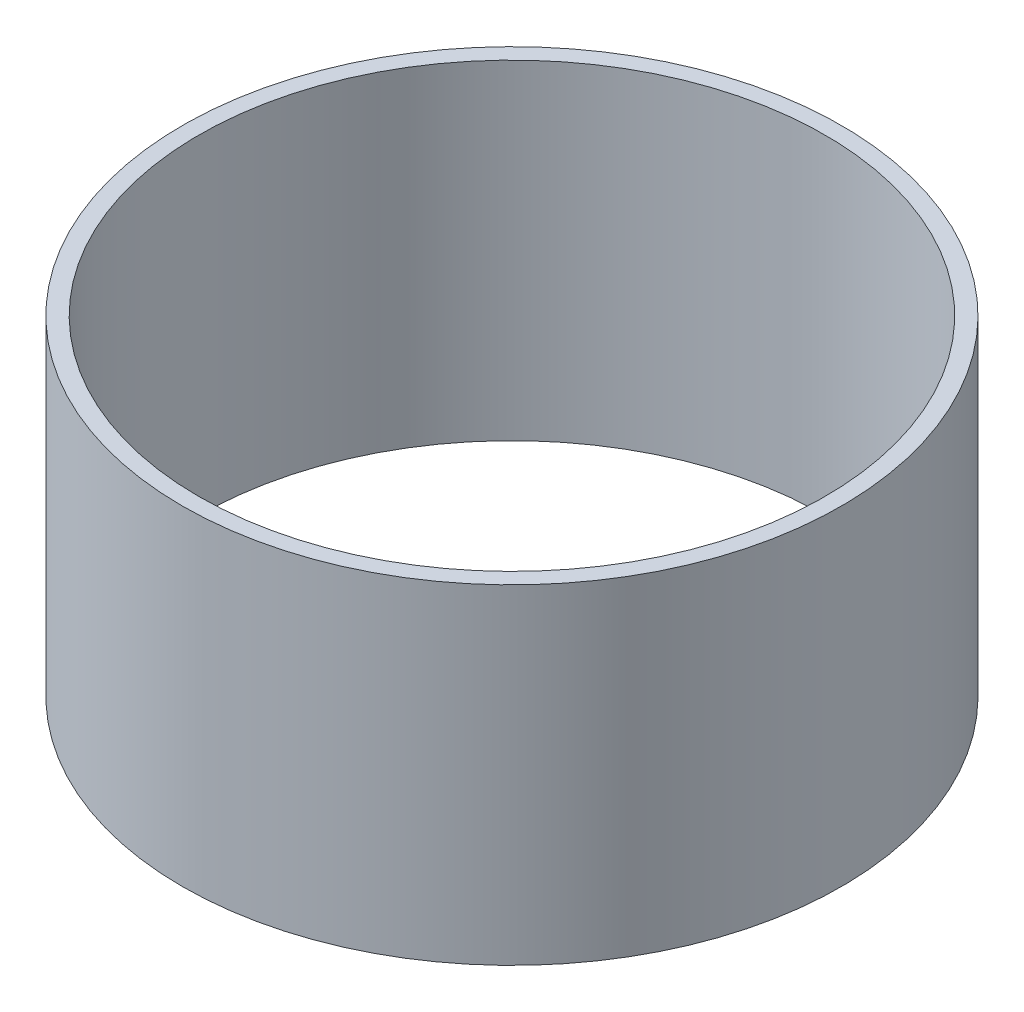
SolidWorks part; units mm, degrees
ref_plane "Front Plane" through (0, 0, 0) normal (0, 0, 1) x (1, 0, 0)
ref_plane "Top Plane" through (0, 0, 0) normal (0, 1, 0) x (1, 0, 0)
ref_plane "Right Plane" through (0, 0, 0) normal (1, 0, 0) x (0, 0, -1)
sketch "Sketch2" plane through (0, 0, 0) normal (0, 1, 0) x (1, 0, 0)
  circle A0 centre (0, 0) radius 380
  circle A1 centre (0, 0) radius 400
  dimension "D1" = 800
  dimension "D2" = 20
extrude "Boss-Extrude1" add sketch "Sketch2" along normal blind 400
